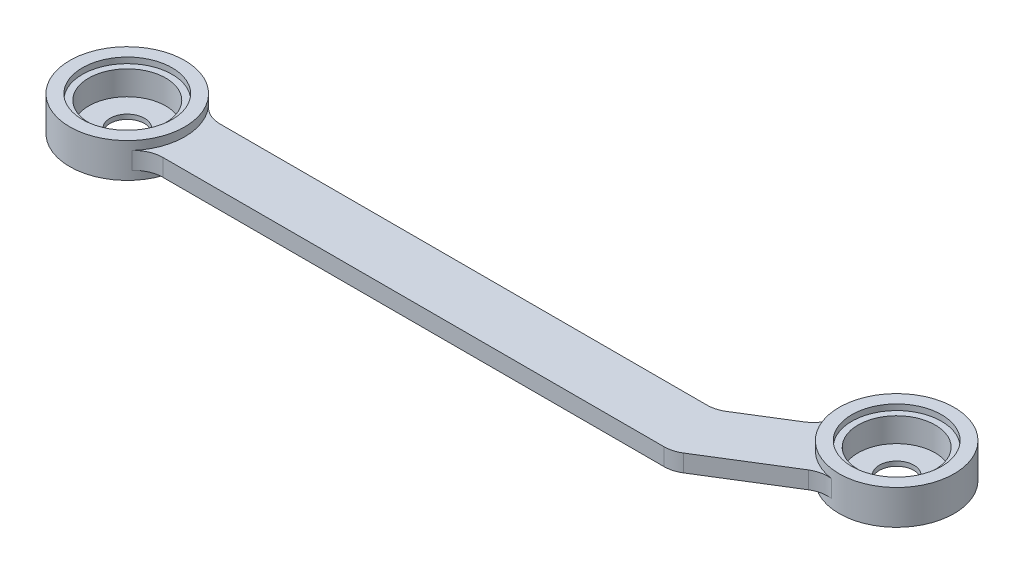
SolidWorks part; units mm, degrees
ref_plane "Front" through (0, 0, 0) normal (0, 0, 1) x (1, 0, 0)
ref_plane "Top" through (0, 0, 0) normal (0, 1, 0) x (1, 0, 0)
ref_plane "Right" through (0, 0, 0) normal (1, 0, 0) x (0, 0, -1)
sketch "Sketch1" plane through (0, 0, 0) normal (0, 1, 0) x (1, 0, 0)
  line L0 (-21.0837, 0) -> (7.8, 0) construction
  line L1 (11.1803, 5) -> (95.7875, 5)
  line L3 (11.1803, -5) -> (98.3185, -5)
  line L4 (98.4229, 5.7509) -> (106.7441, 10.9121)
  line L6 (100.9539, -4.2491) -> (114.3358, 4.0509)
  line L7 (95.48, 0) -> (133.943, 0) construction
  circle A0 centre (0, 0) radius 7.8
  circle A1 centre (119.1, 14.65) radius 7.8
  circle A2 centre (0, 0) radius 3
  circle A3 centre (119.1, 14.65) radius 3
  arc A4 (7.4536, 6.6667) -> (7.4536, -6.6667) centre (0, 0) ccw
  arc A5 (117.6808, 4.7512) -> (109.1058, 14.9907) centre (119.1, 14.65) ccw
  arc A6 (109.1058, 14.9907) -> (106.7441, 10.9121) centre (104.1087, 15.1611) cw
  arc A7 (114.3358, 4.0509) -> (117.6808, 4.7512) centre (116.9712, -0.1982) cw
  arc A8 (100.9539, -4.2491) -> (98.3185, -5) centre (98.3185, 0) cw
  arc A9 (98.4229, 5.7509) -> (95.7875, 5) centre (95.7875, 10) cw
  arc A10 (11.1803, -5) -> (7.4536, -6.6667) centre (11.1803, -10) ccw
  arc A11 (7.4536, 6.6667) -> (11.1803, 5) centre (11.1803, 10) ccw
  point P14 (101.922, -6.3918)
  point P18 (93.2167, 4.9724)
  point P21 (86.1004, 4.9724)
  point P22 (94.834, 5.5464)
  point P23 (92.8012, 5.2468)
  point P24 (109.3303, 12.5161)
  point P27 (116.0632, 5.1223)
  point P34 (8.6603, -5)
  point P37 (8.6603, 5)
  dimension "D1" = 15.6
  dimension "D2" = 15.6
  dimension "D5" = 20
  dimension "D6" = 20
  dimension "D8" = 5
  dimension "D3" = 119.1
  dimension "D4" = 14.65
  dimension "D7" = 10
  dimension "D10" = 10
extrude "Boss-Extrude2" add sketch "Sketch1" along normal mid plane 6 contours A0 A2 | A11 A4 A10 L3 A8 L6 A7 A5 A6 L4 A9 L1 A1 A0 | A1 A3
sketch "Sketch2" plane through (0, 3, 0) normal (0, 1, 0) x (1, 0, 0)
  line L4 (11.1803, -5) -> (98.3185, -5)
  line L5 (100.9539, -4.2491) -> (114.3358, 4.0509)
  line L6 (106.7441, 10.9121) -> (98.4229, 5.7509)
  line L7 (95.7875, 5) -> (11.1803, 5)
  line L8 (11.1803, -5) -> (98.3185, -5)
  line L9 (100.9539, -4.2491) -> (114.3358, 4.0509)
  line L10 (106.7441, 10.9121) -> (98.4229, 5.7509)
  line L11 (95.7875, 5) -> (11.1803, 5)
  circle A0 centre (119.1, 14.65) radius 7.8 construction
  circle A1 centre (0, 0) radius 7.8 construction
  circle A2 centre (119.1, 14.65) radius 7.8
  circle A3 centre (0, 0) radius 7.8
  arc A8 (7.4536, 6.6667) -> (11.1803, 5) centre (11.1803, 10) ccw
  arc A9 (7.4536, 6.6667) -> (7.4536, -6.6667) centre (0, 0) ccw
  arc A10 (11.1803, -5) -> (7.4536, -6.6667) centre (11.1803, -10) ccw
  arc A11 (98.3185, -5) -> (100.9539, -4.2491) centre (98.3185, 0) ccw
  arc A12 (117.6808, 4.7512) -> (114.3358, 4.0509) centre (116.9712, -0.1982) ccw
  arc A13 (117.6808, 4.7512) -> (109.1058, 14.9907) centre (119.1, 14.65) ccw
  arc A14 (106.7441, 10.9121) -> (109.1058, 14.9907) centre (104.1087, 15.1611) ccw
  arc A15 (95.7875, 5) -> (98.4229, 5.7509) centre (95.7875, 10) ccw
  arc A16 (7.4536, 6.6667) -> (11.1803, 5) centre (11.1803, 10) ccw
  arc A17 (7.4536, 6.6667) -> (7.4536, -6.6667) centre (0, 0) ccw
  arc A18 (11.1803, -5) -> (7.4536, -6.6667) centre (11.1803, -10) ccw
  arc A19 (98.3185, -5) -> (100.9539, -4.2491) centre (98.3185, 0) ccw
  arc A20 (117.6808, 4.7512) -> (114.3358, 4.0509) centre (116.9712, -0.1982) ccw
  arc A21 (117.6808, 4.7512) -> (109.1058, 14.9907) centre (119.1, 14.65) ccw
  arc A22 (106.7441, 10.9121) -> (109.1058, 14.9907) centre (104.1087, 15.1611) ccw
  arc A23 (95.7875, 5) -> (98.4229, 5.7509) centre (95.7875, 10) ccw
  dimension "D1" = 0
extrude "Cut-Extrude1" cut sketch "Sketch2" against normal blind 1 contours A3 | A2
sketch "Sketch3" plane through (0, 3, 0) normal (0, 1, 0) x (1, 0, 0)
  circle A0 centre (0, 0) radius 6.7
  circle A1 centre (119.1, 14.65) radius 6.7
extrude "Cut-Extrude2" cut sketch "Sketch3" against normal blind 5.2
sketch "Sketch4" plane through (0, 3, 0) normal (0, 1, 0) x (1, 0, 0)
  line L0 (0, 0) -> (98.3185, 0) construction
  line L1 (98.3185, 0) -> (119.1, 14.65) construction
  line L2 (98.4229, 5.7509) -> (106.7441, 10.9121) construction
  line L3 (100.9539, -4.2491) -> (114.3358, 4.0509) construction
  line L4 (11.1803, -5) -> (98.3185, -5) construction
  line L5 (11.1803, 5) -> (95.7875, 5) construction
  line L6 (98.4229, 5.7509) -> (106.7441, 10.9121)
  line L7 (100.9539, -4.2491) -> (114.3358, 4.0509)
  line L8 (11.1803, -5) -> (98.3185, -5)
  line L9 (11.1803, 5) -> (95.7875, 5)
  line L14 (11.1803, -5) -> (98.3185, -5)
  line L15 (100.9539, -4.2491) -> (114.3358, 4.0509)
  line L16 (106.7441, 10.9121) -> (98.4229, 5.7509)
  line L17 (95.7875, 5) -> (11.1803, 5)
  line L18 (11.1803, -5) -> (98.3185, -5)
  line L19 (100.9539, -4.2491) -> (114.3358, 4.0509)
  line L20 (106.7441, 10.9121) -> (98.4229, 5.7509)
  line L21 (95.7875, 5) -> (11.1803, 5)
  circle A0 centre (0, 0) radius 10
  circle A1 centre (119.1, 14.65) radius 10
  arc A2 (106.7441, 10.9121) -> (109.1058, 14.9907) centre (104.1087, 15.1611) ccw construction
  arc A3 (95.7875, 5) -> (98.4229, 5.7509) centre (95.7875, 10) ccw construction
  arc A4 (98.3185, -5) -> (100.9539, -4.2491) centre (98.3185, 0) ccw construction
  arc A5 (11.1803, -5) -> (7.4536, -6.6667) centre (11.1803, -10) ccw construction
  arc A6 (7.4536, 6.6667) -> (11.1803, 5) centre (11.1803, 10) ccw construction
  arc A7 (106.7441, 10.9121) -> (109.1058, 14.9907) centre (104.1087, 15.1611) ccw
  arc A8 (95.7875, 5) -> (98.4229, 5.7509) centre (95.7875, 10) ccw
  arc A9 (98.3185, -5) -> (100.9539, -4.2491) centre (98.3185, 0) ccw
  arc A10 (11.1803, -5) -> (7.4536, -6.6667) centre (11.1803, -10) ccw
  arc A11 (7.4536, 6.6667) -> (11.1803, 5) centre (11.1803, 10) ccw
  arc A20 (7.4536, 6.6667) -> (11.1803, 5) centre (11.1803, 10) ccw
  arc A21 (7.4536, 6.6667) -> (7.4536, -6.6667) centre (0, 0) ccw
  arc A22 (11.1803, -5) -> (7.4536, -6.6667) centre (11.1803, -10) ccw
  arc A23 (98.3185, -5) -> (100.9539, -4.2491) centre (98.3185, 0) ccw
  arc A24 (117.6808, 4.7512) -> (114.3358, 4.0509) centre (116.9712, -0.1982) ccw
  arc A25 (117.6808, 4.7512) -> (109.1058, 14.9907) centre (119.1, 14.65) ccw
  arc A26 (106.7441, 10.9121) -> (109.1058, 14.9907) centre (104.1087, 15.1611) ccw
  arc A27 (95.7875, 5) -> (98.4229, 5.7509) centre (95.7875, 10) ccw
  arc A28 (7.4536, 6.6667) -> (11.1803, 5) centre (11.1803, 10) ccw
  arc A29 (7.4536, 6.6667) -> (7.4536, -6.6667) centre (0, 0) ccw
  arc A30 (11.1803, -5) -> (7.4536, -6.6667) centre (11.1803, -10) ccw
  arc A31 (98.3185, -5) -> (100.9539, -4.2491) centre (98.3185, 0) ccw
  arc A32 (117.6808, 4.7512) -> (114.3358, 4.0509) centre (116.9712, -0.1982) ccw
  arc A33 (117.6808, 4.7512) -> (109.1058, 14.9907) centre (119.1, 14.65) ccw
  arc A34 (106.7441, 10.9121) -> (109.1058, 14.9907) centre (104.1087, 15.1611) ccw
  arc A35 (95.7875, 5) -> (98.4229, 5.7509) centre (95.7875, 10) ccw
  point P6 (98.3185, 0)
  point P7 (98.3185, 0)
  point P10 (98.3185, 0)
  point P11 (116.0632, 5.1223)
  arc M4 (11.1803, 5) -> (7.4536, 6.6667) centre (11.1803, 10) cw
  arc M6 (7.4536, -6.6667) -> (11.1803, -5) centre (11.1803, -10) cw
  line M7 (11.1803, -5) -> (98.3185, -5)
  arc M8 (98.3185, -5) -> (100.9539, -4.2491) centre (98.3185, 0) ccw
  line M9 (100.9539, -4.2491) -> (114.3358, 4.0509)
  arc M10 (114.3358, 4.0509) -> (117.6808, 4.7512) centre (116.9712, -0.1982) cw
  arc M12 (109.1058, 14.9907) -> (106.7441, 10.9121) centre (104.1087, 15.1611) cw
  line M13 (106.7441, 10.9121) -> (98.4229, 5.7509)
  arc M14 (98.4229, 5.7509) -> (95.7875, 5) centre (95.7875, 10) cw
  line M15 (95.7875, 5) -> (11.1803, 5)
  dimension "D1" = 0
extrude "Cut-Extrude4" cut sketch "Sketch4" against normal blind 1.5 contours A1 A0 M12 M13 M14 M15 M4 M6 M7 M8 M9 M10
sketch "Sketch5" plane through (0, -3, 0) normal (0, -1, 0) x (1, 0, 0)
  line L0 (0, 0) -> (98.3185, 0)
  line L1 (100.9539, 4.2491) -> (114.3358, -4.0509) construction
  line L2 (98.4229, -5.7509) -> (106.7441, -10.9121) construction
  line L3 (11.1803, -5) -> (95.7875, -5) construction
  line L4 (11.1803, 5) -> (98.3185, 5) construction
  line L5 (100.9539, 4.2491) -> (114.3358, -4.0509)
  line L6 (98.4229, -5.7509) -> (106.7441, -10.9121)
  line L7 (11.1803, -5) -> (95.7875, -5)
  line L8 (11.1803, 5) -> (98.3185, 5)
  circle A0 centre (0, 0) radius 10
  circle A1 centre (119.1, -14.65) radius 10
  arc A2 (114.3358, -4.0509) -> (117.6808, -4.7512) centre (116.9712, 0.1982) ccw construction
  arc A3 (109.1058, -14.9907) -> (106.7441, -10.9121) centre (104.1087, -15.1611) ccw construction
  arc A4 (100.9539, 4.2491) -> (98.3185, 5) centre (98.3185, 0) ccw construction
  arc A5 (98.4229, -5.7509) -> (95.7875, -5) centre (95.7875, -10) ccw construction
  arc A6 (114.3358, -4.0509) -> (117.6808, -4.7512) centre (116.9712, 0.1982) ccw
  arc A7 (109.1058, -14.9907) -> (106.7441, -10.9121) centre (104.1087, -15.1611) ccw
  arc A8 (100.9539, 4.2491) -> (98.3185, 5) centre (98.3185, 0) ccw
  arc A9 (98.4229, -5.7509) -> (95.7875, -5) centre (95.7875, -10) ccw
  point P6 (8.6603, -5)
extrude "Cut-Extrude5" cut sketch "Sketch5" against normal blind 1.5
